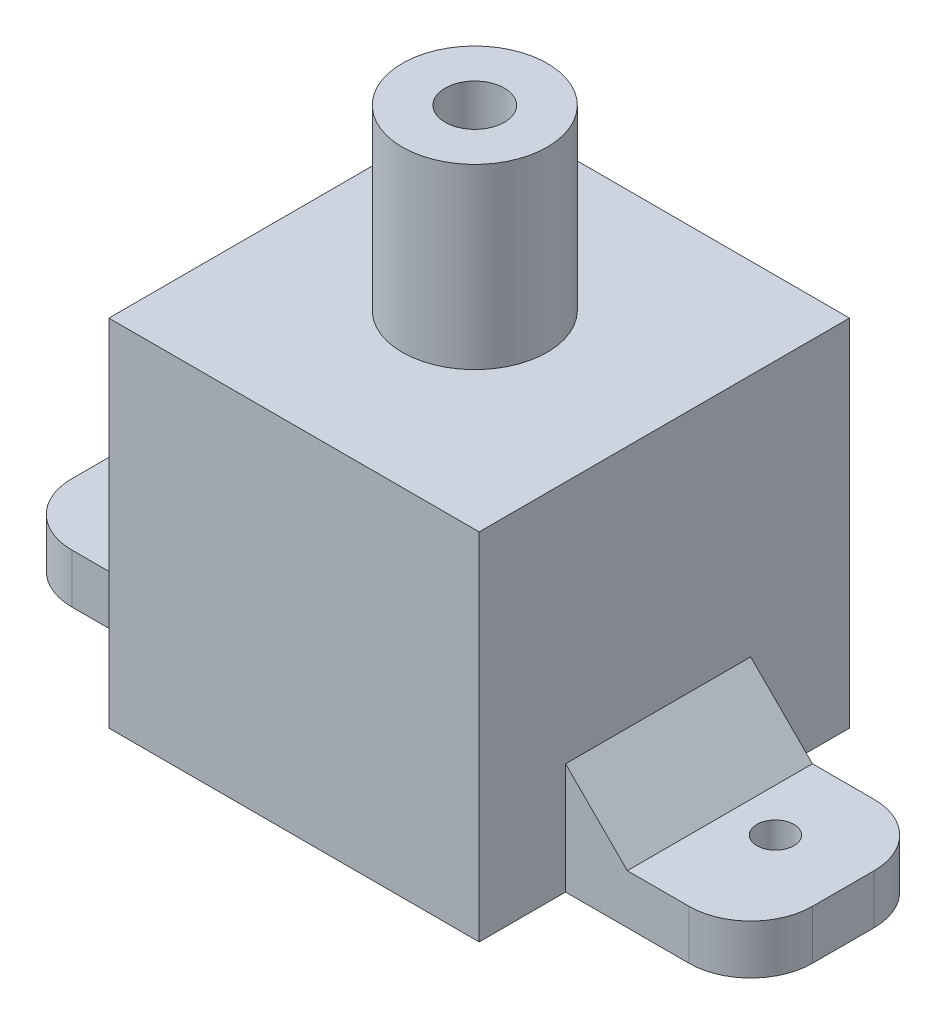
SolidWorks part; units mm, degrees
ref_plane "Спереди" through (0, 0, 0) normal (0, 0, 1) x (1, 0, 0)
ref_plane "Сверху" through (0, 0, 0) normal (0, 1, 0) x (1, 0, 0)
ref_plane "Справа" through (0, 0, 0) normal (1, 0, 0) x (0, 0, -1)
other "Configuration Table"
sketch "Эскиз1" plane through (0, 0, 0) normal (0, 1, 0) x (1, 0, 0)
  line L1 (-14.2865, 14.6433) -> (15.7135, 14.6433)
  line L2 (-14.2865, 14.6433) -> (-14.2865, -15.3567)
  line L3 (-14.2865, -15.3567) -> (15.7135, -15.3567)
  line L4 (15.7135, 14.6433) -> (15.7135, -15.3567)
  dimension "D1" = 30
  dimension "D2" = 30
extrude "высота " add sketch "Эскиз1" along normal blind 28.77
sketch "Эскиз2" plane through (0, 28.77, 0) normal (0, 1, 0) x (1, 0, 0)
  circle A0 centre (0, 0) radius 5.875
  dimension "D1" = 11.75
sketch "Эскиз3" plane through (0, 0, 0) normal (0, 0, 1) x (1, 0, 0)
  line L0 (0, 49.97) -> (0, -1.7648) construction
extrude "Бобышка-Вытянуть2" add sketch "Эскиз2" along normal blind 14.4 contours A0
sketch "Эскиз4" plane through (0, 43.17, 0) normal (0, 1, 0) x (1, 0, 0)
  circle A0 centre (0, 0) radius 2.4
  dimension "D1" = 4.8
sketch "Эскиз5" plane through (0, 0, 0) normal (0, -1, 0) x (1, 0, 0)
  line L0 (15.7135, 15.3567) -> (15.7135, -14.6433) construction
  line L1 (15.7135, 8.3567) -> (25.7135, 8.3567)
  line L2 (15.7135, 8.3567) -> (15.7135, -6.6433)
  line L3 (15.7135, -6.6433) -> (25.7135, -6.6433)
  line L4 (30.7135, 3.3567) -> (30.7135, -1.6433)
  line L5 (15.7135, -14.6433) -> (-14.2865, -14.6433) construction
  line L6 (0, 0) -> (0, -14.6433) construction
  line L12 (-14.2865, -14.6433) -> (-14.2865, 15.3567) construction
  line L13 (-14.2865, 8.3567) -> (-24.2865, 8.3567)
  line L14 (-14.2865, 8.3567) -> (-14.2865, -6.6433)
  line L15 (-14.2865, -6.6433) -> (-24.2865, -6.6433)
  line L16 (-29.2865, 3.3567) -> (-29.2865, -1.6433)
  arc A0 (-29.2865, 3.3567) -> (-24.2865, 8.3567) centre (-24.2865, 3.3567) cw
  arc A1 (-24.2865, -6.6433) -> (-29.2865, -1.6433) centre (-24.2865, -1.6433) cw
  arc A2 (30.7135, 3.3567) -> (25.7135, 8.3567) centre (25.7135, 3.3567) ccw
  arc A3 (30.7135, -1.6433) -> (25.7135, -6.6433) centre (25.7135, -1.6433) cw
  point P19 (-29.2865, 8.3567)
  point P22 (-29.2865, -6.6433)
  point P25 (30.7135, 8.3567)
  point P28 (30.7135, -6.6433)
  dimension "D7" = 5
  dimension "D8" = 5
  dimension "D9" = 5
  dimension "D10" = 5
  dimension "D1" = 15
  dimension "D2" = 15
  dimension "D3" = 8
  dimension "D4" = 15
  dimension "D5" = 15
  dimension "D6" = 8
extrude "Бобышка-Вытянуть4" add sketch "Эскиз5" against normal blind 4
sketch "Эскиз6" plane through (0, 4, 0) normal (0, 1, 0) x (1, 0, 0)
  line L0 (30.7135, 1.6433) -> (30.7135, -3.3567) construction
  line L1 (15.7135, 6.6433) -> (25.7135, 6.6433) construction
  line L2 (-24.2865, 6.6433) -> (-14.2865, 6.6433) construction
  line L3 (-29.2865, -3.3567) -> (-29.2865, 1.6433) construction
  circle A0 centre (24.2135, 0.1433) radius 1.5
  circle A1 centre (-22.7865, 0.1433) radius 1.5
  dimension "D1" = 3
  dimension "D4" = 3
  dimension "D2" = 6.5
  dimension "D3" = 6.5
  dimension "D5" = 6.5
  dimension "D6" = 6.5
extrude "Вырез-Вытянуть2" cut sketch "Эскиз6" against normal through all both and the other way through all contours A1 | A0
chamfer "Фаска2" distance 5 angle 45 1 edges at (15.7135, 4, 0.8567)
chamfer "Фаска3" distance 5 angle 45 1 edges at (-14.2865, 4, 0.8567)
extrude "Вырез-Вытянуть3" cut sketch "Эскиз4" against normal blind 8 contours A0
